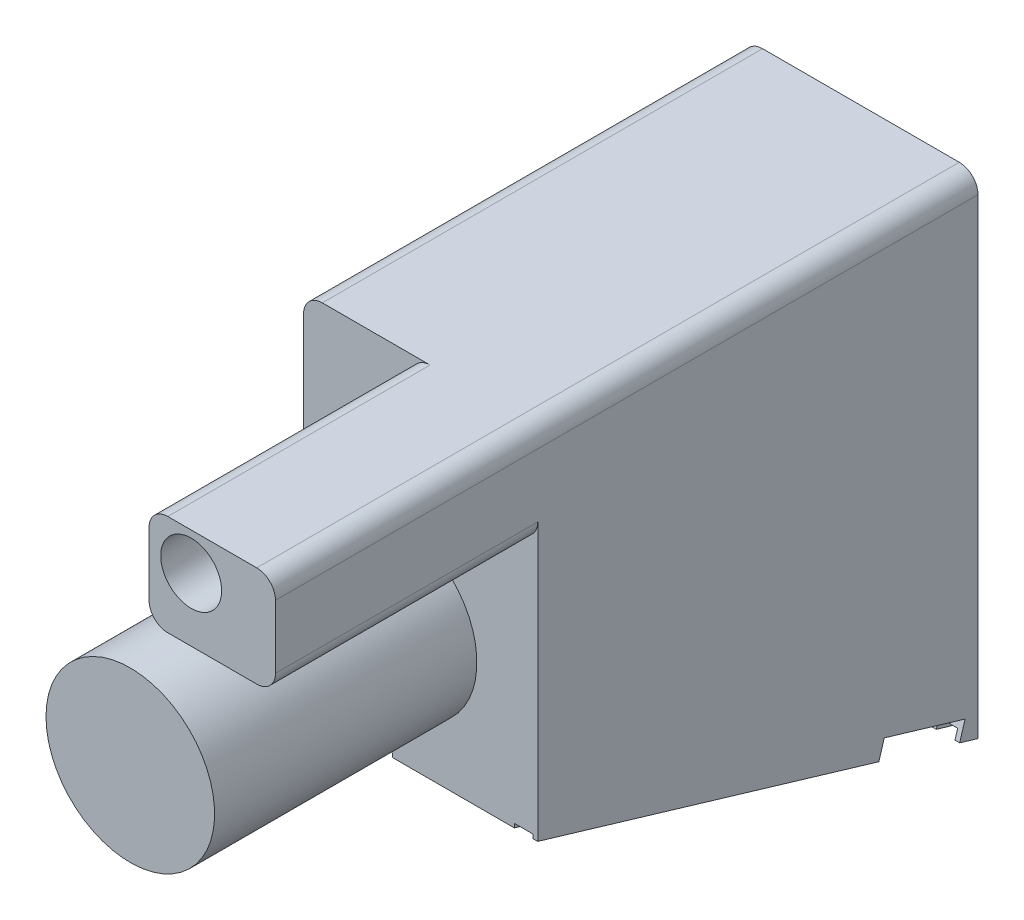
SolidWorks part; units mm, degrees
material "ABS"
ref_plane "Спереди" through (0, 0, 0) normal (0, 0, 1) x (1, 0, 0)
ref_plane "Сверху" through (0, 0, 0) normal (0, 1, 0) x (1, 0, 0)
ref_plane "Справа" through (0, 0, 0) normal (1, 0, 0) x (0, 0, -1)
sketch "Эскиз1" plane through (0, 0, 0) normal (0, 0, 1) x (1, 0, 0)
  line L1 (12.5, -30) -> (-12.5, -30)
  line L2 (12.5, -30) -> (12.5, 30)
  line L3 (12.5, 30) -> (-12.5, 30)
  line L4 (-12.5, -30) -> (-12.5, 30)
  line L5 (12.5, -30) -> (-12.5, 30) construction
  line L6 (12.5, 30) -> (-12.5, -30) construction
  point P0 (0, 0)
  dimension "D1" = 25
  dimension "D2" = 60
extrude "Бобышка-Вытянуть1" add sketch "Эскиз1" along normal blind 75
sketch "фокусные расстояния" plane through (12.5, 0, 0) normal (1, 0, 0) x (0, 0, -1)
  line L0 (-52, 22.5) -> (8, 22.5)
  line L1 (-52, 15) -> (-52, 30) construction
  line L2 (8, 22.5) -> (-6.2668, -25.4214)
  line L3 (0, -30) -> (0, 30) construction
  line L4 (0, 0) -> (-47, 0) construction
  line L5 (-66, -15) -> (-47, -15) construction
  line L6 (-66, -15) -> (-66, 15)
  line L7 (-66, 15) -> (-47, 15) construction
  line L8 (-47, -15) -> (-47, 15) construction
  line L9 (-47, -13.2946) -> (-6.2668, -25.4214)
  line L11 (-121.1502, -9) -> (-47, -9) construction
  line L12 (-121.1502, -9) -> (-121.1502, 9) construction
  line L13 (-121.1502, 9) -> (-47, 9) construction
  line L14 (-47, -9) -> (-47, 9) construction
  line L15 (-75, 30) -> (0, 30) construction
  point P18 (-47, 0)
  point P22 (-52, 22.5)
  dimension "D1" = 60
  dimension "D2" = 8
  dimension "D3" = 50
  dimension "D4" = 30
  dimension "D5" = 42.5
  dimension "D6" = 55
  dimension "D7" = 18
  dimension "D8" = 19
ref_plane "Плоскость1" through (0, 0, 47) normal (0, 0, 1) x (1, 0, 0)
sketch "Эскиз3" plane through (0, 0, 47) normal (0, 0, 1) x (1, 0, 0)
  line L0 (12.5, -30) -> (12.5, 30) construction
  line L1 (12.5, -30) -> (12.5, 30)
  line L2 (-12.5, -30) -> (12.5, -30) construction
  line L3 (-12.5, -30) -> (12.5, -30)
  line L4 (-12.5, 30) -> (-12.5, -30) construction
  line L5 (-12.5, 30) -> (-12.5, -30)
  line L6 (12.5, 30) -> (-12.5, 30) construction
  line L7 (12.5, 30) -> (-12.5, 30)
  line L8 (-12.5, 14.25) -> (-1, 14.25) construction
  line L9 (-1, 14.25) -> (-1, 30)
  line L10 (-1, 14.25) -> (12.5, 14.25)
  line L11 (3.5, 30) -> (3.5, 14.25) construction
  line L12 (0, 0) -> (-3, 0) construction
  circle A0 centre (-3, 0) radius 9
  circle A1 centre (3.5, 21) radius 3.25 construction
  dimension "D1" = 18
  dimension "D5" = 6.5
  dimension "D2" = 14.25
  dimension "D3" = 2
  dimension "D4" = 6.5
  dimension "D6" = 21
  dimension "D7" = 9
extrude "Вырез-Вытянуть1" cut sketch "Эскиз3" along normal through all contours L10 L9 L7 L5 L3 L1 A0
ref_plane "Плоскость3" through (0, 0, 52) normal (0, 0, 1) x (1, 0, 0)
sketch "Эскиз4" plane through (0, 0, 52) normal (0, 0, 1) x (1, 0, 0)
  circle A0 centre (3.5, 21) radius 3.25 construction
  circle A1 centre (3.5, 21) radius 3.25
extrude "Вырез-Вытянуть2" cut sketch "Эскиз4" along normal through all
sketch "Эскиз5" plane through (0, 0, 52) normal (0, 0, 1) x (1, 0, 0)
  circle A0 centre (3.5, 21) radius 3.25 construction
  circle A1 centre (3.5, 21) radius 3.25 construction
  circle A2 centre (3.5, 21) radius 1.5
  dimension "D1" = 3
extrude "Вырез-Вытянуть3" cut sketch "Эскиз5" against normal through all
sketch "Эскиз6" plane through (0, 0, 0) normal (0, 0, -1) x (-1, 0, 0)
  line L0 (-12.5, -30) -> (-12.5, 30) construction
  line L1 (12.5, 30) -> (-12.5, 30)
  line L2 (12.5, 30) -> (12.5, 25)
  line L3 (12.5, 25) -> (-12.5, 25)
  line L4 (-12.5, 30) -> (-12.5, 25)
  circle A0 centre (3, 0) radius 9 construction
  circle A1 centre (3, 0) radius 9 construction
  dimension "D1" = 25
extrude "Вырез-Вытянуть4" cut sketch "Эскиз6" against normal through all
sketch "Эскиз8" plane through (12.5, 0, 0) normal (1, 0, 0) x (0, 0, -1)
  line L0 (-47, -13.2946) -> (-6.2668, -25.4214) construction
  line L1 (-47, -13.2946) -> (-6.2668, -25.4214) construction
  line L2 (-47, -13.2946) -> (0, -27.2871)
  line L3 (0, -30) -> (0, 25) construction
  line L4 (-47, -30) -> (-47, 14.25) construction
  line L5 (-47, -30) -> (-47, 14.25)
  line L6 (-47, -30) -> (0, -30) construction
  line L7 (-47, -30) -> (0, -30)
  line L8 (0, -30) -> (0, 25)
  line M2 (0, -30) -> (0, 25)
  line M6 (-47, 14.25) -> (-47, -30)
  line M7 (-47, -30) -> (0, -30)
extrude "Вырез-Вытянуть5" cut sketch "Эскиз8" against normal through all contours L2 M6 M7 M2
sketch "Эскиз9" plane through (0, -25.0655, 7.4623) normal (0, -0.9584, 0.2853) x (1, 0, 0)
  line L0 (12.5, -1.2473) -> (-12.5, -1.2473) construction
  line L1 (-12.5, 41.2527) -> (-12.5, -7.786) construction
  line L3 (3.5, 5.9921) -> (3.5, -1.2473) construction
  circle A0 centre (3.5, -1.2473) radius 3
  ellipse E0 centre (3.5, 5.9921) end of major axis (5, 5.9921) minor radius 0.428 construction
  ellipse E1 centre (3.5, 5.9921) end of major axis (5, 5.9921) minor radius 0.428 construction
  dimension "D1" = 6
extrude "Вырез-Вытянуть6" cut sketch "Эскиз9" against normal through all
sketch "Эскиз10" plane through (0, -25.0655, 7.4623) normal (0, -0.9584, 0.2853) x (1, 0, 0)
  line L1 (8.5, -6.2473) -> (-1.5, -6.2473)
  line L2 (8.5, -6.2473) -> (8.5, 3.7527)
  line L3 (8.5, 3.7527) -> (-1.5, 3.7527)
  line L4 (-1.5, -6.2473) -> (-1.5, 3.7527)
  line L5 (8.5, -6.2473) -> (-1.5, 3.7527) construction
  line L6 (8.5, 3.7527) -> (-1.5, -6.2473) construction
  point P0 (3.5, -1.2473)
  dimension "D1" = 10
  dimension "D2" = 10
extrude "Вырез-Вытянуть7" cut sketch "Эскиз10" against normal blind 5
sketch "Эскиз11" plane through (-1.5, 0, 0) normal (1, 0, 0) x (0, 0, -1)
  line L0 (-10.5798, -24.1374) -> (-1.9539, -26.7054)
  line L1 (-10.5798, -24.1374) -> (-10.0091, -22.2205)
  line L2 (-1.9539, -26.7054) -> (-1.3832, -24.7885)
  line L3 (-10.0091, -22.2205) -> (-1.3832, -24.7885)
  line L4 (-11.059, -23.9947) -> (-1.4747, -26.848) construction
  point P6 (-6.2668, -25.4214)
  point P8 (-6.2668, -25.4214)
  dimension "D1" = 9
  dimension "D2" = 2
extrude "Вырез-Вытянуть8" cut sketch "Эскиз11" against normal blind 5 and the other way blind 15
sketch "Эскиз12" plane through (0, -25.0655, 7.4623) normal (0, -0.9584, 0.2853) x (1, 0, 0)
  line L0 (3.5, -1.2473) -> (3.5, 41.2527) construction
  line L1 (-12.5, 41.2527) -> (12.5, 41.2527) construction
  line L2 (-12.5, 39.7527) -> (12.5489, 39.7527) construction
  line L3 (-12.5, 41.2527) -> (-12.5, -7.786) construction
  line L4 (12.5, 41.2527) -> (12.5, 3.2527) construction
  circle A0 centre (3.5, -1.2473) radius 3 construction
  circle A1 centre (3.5, -1.2473) radius 3 construction
  circle A2 centre (-4, 39.7527) radius 1
  circle A3 centre (11, 39.7527) radius 1
  dimension "D2" = 2
  dimension "D1" = 41
  dimension "D3" = 15
  dimension "D4" = 9
extrude "Вырез-Вытянуть9" cut sketch "Эскиз12" against normal blind 10
ref_plane "Плоскость2" through (0, -2.2216, -7.4623) normal (0, -0.2853, -0.9584) x (1, 0, 0)
sketch "Эскиз14" plane through (0, -55.1162, 8.2851) normal (0, 0.2853, 0.9584) x (-1, 0, 0)
  line L0 (1.5, -29.0362) -> (-8.5, -29.0362) construction
  line L1 (1.5, -29.0362) -> (-8.5, -29.0362) construction
  line L2 (-3.5, -29.0362) -> (-3.5, -26.5635) construction
  line L4 (12.5, -29.0362) -> (-12.5, -29.0362) construction
  line L5 (5, -29.0362) -> (3, -29.0362)
  line L6 (5, -29.0362) -> (5, -30.0362)
  line L7 (5, -30.0362) -> (3, -30.0362)
  line L8 (3, -29.0362) -> (3, -30.0362)
  line L9 (-10, -29.0362) -> (-10, -30.0362)
  line L10 (-12, -30.0362) -> (-10, -30.0362)
  line L11 (-12, -29.0362) -> (-12, -30.0362)
  line L12 (-12, -29.0362) -> (-10, -29.0362)
  line L13 (-11, -29.0362) -> (-11, -30.0362) construction
  line L14 (4, -30.0362) -> (4, -29.0362) construction
  dimension "D1" = 2
  dimension "D2" = 1
  dimension "D3" = 15
extrude "Вырез-Вытянуть10" cut sketch "Эскиз14" along normal blind 49.16
sketch "Эскиз15" plane through (0, -25.0655, 7.4623) normal (0, -0.9584, 0.2853) x (1, 0, 0)
  line L1 (-0.9405, 33.7527) -> (2, 33.7527)
  line L2 (-0.9405, 33.7527) -> (-0.9405, 24.7527)
  line L3 (-0.9405, 24.7527) -> (2, 24.7527)
  line L4 (2, 33.7527) -> (2, 24.7527)
  circle A1 centre (-4, 39.7527) radius 1 construction
  dimension "D1" = 2.9405
  dimension "D2" = 6
  dimension "D3" = 6
  dimension "D4" = 15
extrude "Вырез-Вытянуть11" cut sketch "Эскиз15" against normal blind 1
fillet "Скругление1" radius 2 5 edges at (-12.5, 25, 23.5) (-1, 14.25, 61) (-1, 25, 61) (12.5, 14.25, 61) (12.5, 25, 37.5)
